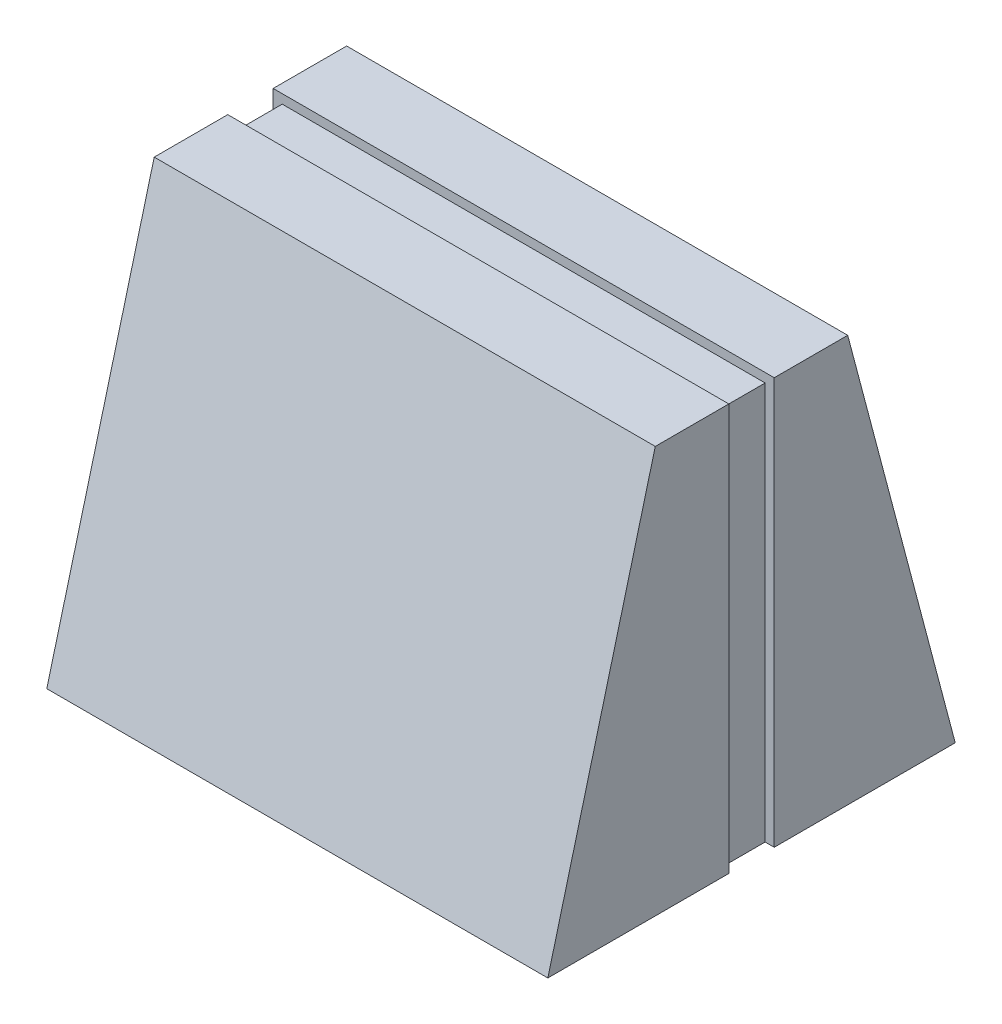
SolidWorks part; units mm, degrees
ref_plane "Front Plane" through (0, 0, 0) normal (0, 0, 1) x (1, 0, 0)
ref_plane "Top Plane" through (0, 0, 0) normal (0, 1, 0) x (1, 0, 0)
ref_plane "Right Plane" through (0, 0, 0) normal (1, 0, 0) x (0, 0, -1)
sketch "Sketch1" plane through (0, 0, 0) normal (0, 1, 0) x (1, 0, 0)
  line L1 (-6.9, -5.61) -> (6.9, -5.61)
  line L2 (-6.9, -5.61) -> (-6.9, 5.61)
  line L3 (-6.9, 5.61) -> (6.9, 5.61)
  line L4 (6.9, -5.61) -> (6.9, 5.61)
  line L5 (-6.9, -5.61) -> (6.9, 5.61) construction
  line L6 (-6.9, 5.61) -> (6.9, -5.61) construction
  point P0 (0, 0)
  dimension "D1" = 13.8
  dimension "D2" = 11.22
ref_plane "Plane1" through (0, 11.2, 0) normal (0, 1, 0) x (1, 0, 0)
sketch "Sketch2" plane through (0, 11.2, 0) normal (0, 1, 0) x (1, 0, 0)
  line L1 (-6.9, -2.651) -> (6.9, -2.651)
  line L2 (-6.9, -2.651) -> (-6.9, 2.649)
  line L3 (-6.9, 2.649) -> (6.9, 2.649)
  line L4 (6.9, -2.651) -> (6.9, 2.649)
  line L5 (-6.9, -2.651) -> (6.9, 2.649) construction
  line L6 (-6.9, 2.649) -> (6.9, -2.651) construction
  line L7 (6.9, -5.61) -> (6.9, 5.61) construction
  dimension "D1" = 5.3
  dimension "D2" = 13.8
loft "Loft1" add profiles "Sketch1", "Sketch2"
sketch "Sketch4" plane through (0, 11.2, 0) normal (0, 1, 0) x (1, 0, 0)
  line L0 (6.9, -2.651) -> (6.9, 2.649) construction
  line L1 (-6.9, -0.625) -> (6.9, -0.625)
  line L2 (-6.9, -0.625) -> (-6.9, 0.625)
  line L3 (-6.9, 0.625) -> (6.9, 0.625)
  line L4 (6.9, -0.625) -> (6.9, 0.625)
  line L5 (-6.9, -0.625) -> (6.9, 0.625) construction
  line L6 (-6.9, 0.625) -> (6.9, -0.625) construction
  point P0 (0, 0)
  dimension "D1" = 1.25
extrude "Cut-Extrude1" cut sketch "Sketch4" against normal blind 0.25
sketch "Sketch5" plane through (6.9, 0, 0) normal (1, 0, 0) x (0, 0, -1)
  line L0 (-5.61, 0) -> (5.61, 0) construction
  line L1 (-0.625, 10.95) -> (0.625, 10.95)
  line L2 (-0.625, 10.95) -> (-0.625, 0)
  line L3 (-0.625, 0) -> (0.625, 0)
  line L4 (0.625, 10.95) -> (0.625, 0)
  dimension "D1" = 1.25
extrude "Cut-Extrude2" cut sketch "Sketch5" against normal blind 0.25
sketch "Sketch6" plane through (-6.9, 0, 0) normal (-1, 0, 0) x (0, 0, 1)
  line L1 (-0.625, 10.95) -> (0.625, 10.95)
  line L2 (-0.625, 10.95) -> (-0.625, 0)
  line L3 (-0.625, 0) -> (0.625, 0)
  line L4 (0.625, 10.95) -> (0.625, 0)
extrude "Cut-Extrude3" cut sketch "Sketch6" against normal blind 0.25
